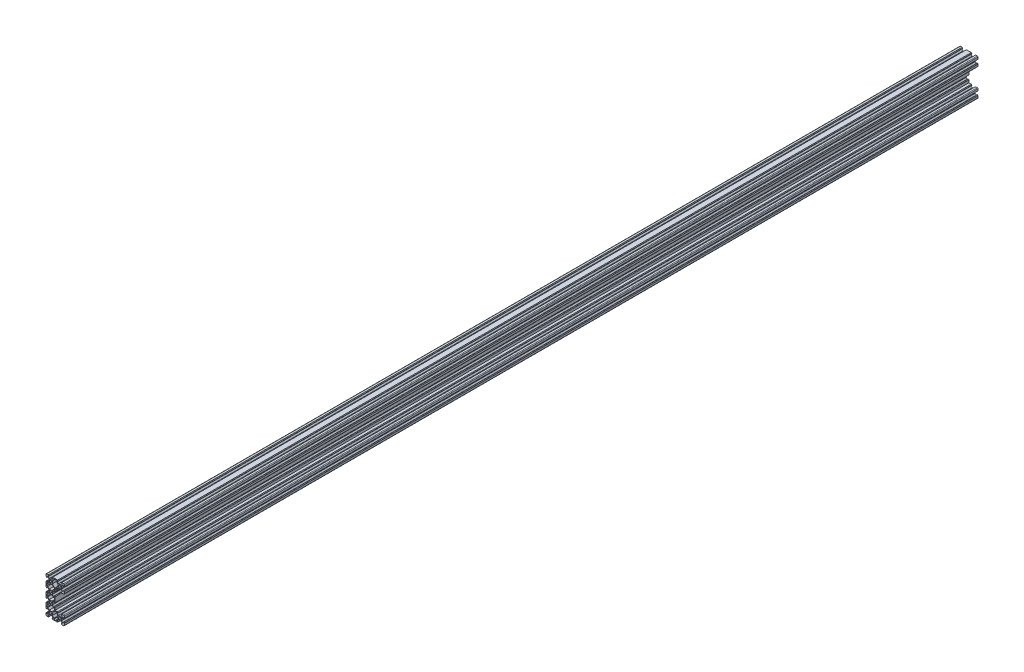
SolidWorks part; units mm, degrees
material "Aluminium"
ref_plane "Front Plane" through (0, 0, 0) normal (0, 0, 1) x (1, 0, 0)
ref_plane "Top Plane" through (0, 0, 0) normal (0, 1, 0) x (1, 0, 0)
ref_plane "Right Plane" through (0, 0, 0) normal (1, 0, 0) x (0, 0, -1)
sketch "Sketch1" plane through (0, 0, 0) normal (0, 0, 1) x (1, 0, 0)
  line L0 (-20, -38.5) -> (-20, 38.5)
  line L1 (-18.5, 40) -> (18.5, 40)
  line L2 (20, 38.5) -> (20, 21.5)
  line L3 (18.5, 20) -> (0, 20)
  line L4 (0, 20) -> (0, -20)
  line L5 (0, 0) -> (-20, 0) construction
  line L6 (18.5, -20) -> (0, -20)
  line L7 (20, -38.5) -> (20, -21.5)
  line L8 (-18.5, -40) -> (18.5, -40)
  line L9 (20, 30) -> (10, 30) construction
  line L10 (-10, 0) -> (-10, 10) construction
  arc A0 (-18.5, -40) -> (-20, -38.5) centre (-18.5, -38.5) cw
  arc A1 (20, -38.5) -> (18.5, -40) centre (18.5, -38.5) cw
  arc A2 (18.5, -20) -> (20, -21.5) centre (18.5, -21.5) cw
  arc A3 (20, 21.5) -> (18.5, 20) centre (18.5, 21.5) cw
  arc A4 (18.5, 40) -> (20, 38.5) centre (18.5, 38.5) cw
  arc A5 (-20, 38.5) -> (-18.5, 40) centre (-18.5, 38.5) cw
  circle A6 centre (10, 30) radius 2.3
  circle A7 centre (-10, 30) radius 2.3
  circle A8 centre (-10, 10) radius 2.3
  circle A9 centre (-10, -10) radius 2.3
  circle A10 centre (10, -30) radius 2.3
  circle A11 centre (-10, -30) radius 2.3
  point P13 (-20, -40)
  point P16 (20, -40)
  point P19 (20, -20)
  point P22 (20, 20)
  point P25 (20, 40)
  point P28 (-20, 40)
  line B0 (-10, 30) -> (-10, 40) construction
  line B1 (-10, 33.69) -> (-10.21, 33.9)
  line B2 (-10.21, 33.9) -> (-12.8393, 33.9)
  line B3 (-12.8393, 33.9) -> (-15.5, 36.5607)
  line B4 (-15.5, 36.5607) -> (-15.5, 38.2)
  line B5 (-15.5, 38.2) -> (-13.395, 38.2)
  line B6 (-13.395, 38.2) -> (-13.395, 38.815)
  line B7 (-13.395, 38.815) -> (-14.58, 40)
  line B8 (-14.58, 40) -> (-5.42, 40)
  line B9 (-10, 30) -> (-15.9132, 35.9132) construction
  line B10 (-6.605, 38.815) -> (-5.42, 40)
  line B11 (-6.605, 38.2) -> (-6.605, 38.815)
  line B12 (-4.5, 38.2) -> (-6.605, 38.2)
  line B13 (-4.5, 36.5607) -> (-4.5, 38.2)
  line B14 (-7.1607, 33.9) -> (-4.5, 36.5607)
  line B15 (-9.79, 33.9) -> (-7.1607, 33.9)
  line B16 (-10, 33.69) -> (-9.79, 33.9)
  line B17 (10, 30) -> (10, 40) construction
  line B18 (10, 33.69) -> (9.79, 33.9)
  line B19 (9.79, 33.9) -> (7.1607, 33.9)
  line B20 (7.1607, 33.9) -> (4.5, 36.5607)
  line B21 (4.5, 36.5607) -> (4.5, 38.2)
  line B22 (4.5, 38.2) -> (6.605, 38.2)
  line B23 (6.605, 38.2) -> (6.605, 38.815)
  line B24 (6.605, 38.815) -> (5.42, 40)
  line B25 (5.42, 40) -> (14.58, 40)
  line B26 (10, 30) -> (4.0868, 35.9132) construction
  line B27 (13.395, 38.815) -> (14.58, 40)
  line B28 (13.395, 38.2) -> (13.395, 38.815)
  line B29 (15.5, 38.2) -> (13.395, 38.2)
  line B30 (15.5, 36.5607) -> (15.5, 38.2)
  line B31 (12.8393, 33.9) -> (15.5, 36.5607)
  line B32 (10.21, 33.9) -> (12.8393, 33.9)
  line B33 (10, 33.69) -> (10.21, 33.9)
  line B34 (10, -30) -> (10, -20) construction
  line B35 (10, -26.31) -> (9.79, -26.1)
  line B36 (9.79, -26.1) -> (7.1607, -26.1)
  line B37 (7.1607, -26.1) -> (4.5, -23.4393)
  line B38 (4.5, -23.4393) -> (4.5, -21.8)
  line B39 (4.5, -21.8) -> (6.605, -21.8)
  line B40 (6.605, -21.8) -> (6.605, -21.185)
  line B41 (6.605, -21.185) -> (5.42, -20)
  line B42 (5.42, -20) -> (14.58, -20)
  line B43 (10, -30) -> (4.0868, -24.0868) construction
  line B44 (13.395, -21.185) -> (14.58, -20)
  line B45 (13.395, -21.8) -> (13.395, -21.185)
  line B46 (15.5, -21.8) -> (13.395, -21.8)
  line B47 (15.5, -23.4393) -> (15.5, -21.8)
  line B48 (12.8393, -26.1) -> (15.5, -23.4393)
  line B49 (10.21, -26.1) -> (12.8393, -26.1)
  line B50 (10, -26.31) -> (10.21, -26.1)
  line B51 (-10, 30) -> (-20, 30) construction
  line B52 (-13.69, 30) -> (-13.9, 29.79)
  line B53 (-13.9, 29.79) -> (-13.9, 27.1607)
  line B54 (-13.9, 27.1607) -> (-16.5607, 24.5)
  line B55 (-16.5607, 24.5) -> (-18.2, 24.5)
  line B56 (-18.2, 24.5) -> (-18.2, 26.605)
  line B57 (-18.2, 26.605) -> (-18.815, 26.605)
  line B58 (-18.815, 26.605) -> (-20, 25.42)
  line B59 (-20, 25.42) -> (-20, 34.58)
  line B60 (-10, 30) -> (-15.9132, 24.0868) construction
  line B61 (-18.815, 33.395) -> (-20, 34.58)
  line B62 (-18.2, 33.395) -> (-18.815, 33.395)
  line B63 (-18.2, 35.5) -> (-18.2, 33.395)
  line B64 (-16.5607, 35.5) -> (-18.2, 35.5)
  line B65 (-13.9, 32.8393) -> (-16.5607, 35.5)
  line B66 (-13.9, 30.21) -> (-13.9, 32.8393)
  line B67 (-13.69, 30) -> (-13.9, 30.21)
  line B68 (-10, 10) -> (-20, 10) construction
  line B69 (-13.69, 10) -> (-13.9, 9.79)
  line B70 (-13.9, 9.79) -> (-13.9, 7.1607)
  line B71 (-13.9, 7.1607) -> (-16.5607, 4.5)
  line B72 (-16.5607, 4.5) -> (-18.2, 4.5)
  line B73 (-18.2, 4.5) -> (-18.2, 6.605)
  line B74 (-18.2, 6.605) -> (-18.815, 6.605)
  line B75 (-18.815, 6.605) -> (-20, 5.42)
  line B76 (-20, 5.42) -> (-20, 14.58)
  line B77 (-10, 10) -> (-15.9132, 4.0868) construction
  line B78 (-18.815, 13.395) -> (-20, 14.58)
  line B79 (-18.2, 13.395) -> (-18.815, 13.395)
  line B80 (-18.2, 15.5) -> (-18.2, 13.395)
  line B81 (-16.5607, 15.5) -> (-18.2, 15.5)
  line B82 (-13.9, 12.8393) -> (-16.5607, 15.5)
  line B83 (-13.9, 10.21) -> (-13.9, 12.8393)
  line B84 (-13.69, 10) -> (-13.9, 10.21)
  line B85 (-10, -10) -> (-20, -10) construction
  line B86 (-13.69, -10) -> (-13.9, -10.21)
  line B87 (-13.9, -10.21) -> (-13.9, -12.8393)
  line B88 (-13.9, -12.8393) -> (-16.5607, -15.5)
  line B89 (-16.5607, -15.5) -> (-18.2, -15.5)
  line B90 (-18.2, -15.5) -> (-18.2, -13.395)
  line B91 (-18.2, -13.395) -> (-18.815, -13.395)
  line B92 (-18.815, -13.395) -> (-20, -14.58)
  line B93 (-20, -14.58) -> (-20, -5.42)
  line B94 (-10, -10) -> (-15.9132, -15.9132) construction
  line B95 (-18.815, -6.605) -> (-20, -5.42)
  line B96 (-18.2, -6.605) -> (-18.815, -6.605)
  line B97 (-18.2, -4.5) -> (-18.2, -6.605)
  line B98 (-16.5607, -4.5) -> (-18.2, -4.5)
  line B99 (-13.9, -7.1607) -> (-16.5607, -4.5)
  line B100 (-13.9, -9.79) -> (-13.9, -7.1607)
  line B101 (-13.69, -10) -> (-13.9, -9.79)
  line B102 (-10, -30) -> (-20, -30) construction
  line B103 (-13.69, -30) -> (-13.9, -30.21)
  line B104 (-13.9, -30.21) -> (-13.9, -32.8393)
  line B105 (-13.9, -32.8393) -> (-16.5607, -35.5)
  line B106 (-16.5607, -35.5) -> (-18.2, -35.5)
  line B107 (-18.2, -35.5) -> (-18.2, -33.395)
  line B108 (-18.2, -33.395) -> (-18.815, -33.395)
  line B109 (-18.815, -33.395) -> (-20, -34.58)
  line B110 (-20, -34.58) -> (-20, -25.42)
  line B111 (-10, -30) -> (-15.9132, -35.9132) construction
  line B112 (-18.815, -26.605) -> (-20, -25.42)
  line B113 (-18.2, -26.605) -> (-18.815, -26.605)
  line B114 (-18.2, -24.5) -> (-18.2, -26.605)
  line B115 (-16.5607, -24.5) -> (-18.2, -24.5)
  line B116 (-13.9, -27.1607) -> (-16.5607, -24.5)
  line B117 (-13.9, -29.79) -> (-13.9, -27.1607)
  line B118 (-13.69, -30) -> (-13.9, -29.79)
  line B119 (-10, -30) -> (-10, -40) construction
  line B120 (-10, -33.69) -> (-9.79, -33.9)
  line B121 (-9.79, -33.9) -> (-7.1607, -33.9)
  line B122 (-7.1607, -33.9) -> (-4.5, -36.5607)
  line B123 (-4.5, -36.5607) -> (-4.5, -38.2)
  line B124 (-4.5, -38.2) -> (-6.605, -38.2)
  line B125 (-6.605, -38.2) -> (-6.605, -38.815)
  line B126 (-6.605, -38.815) -> (-5.42, -40)
  line B127 (-5.42, -40) -> (-14.58, -40)
  line B128 (-10, -30) -> (-4.0868, -35.9132) construction
  line B129 (-13.395, -38.815) -> (-14.58, -40)
  line B130 (-13.395, -38.2) -> (-13.395, -38.815)
  line B131 (-15.5, -38.2) -> (-13.395, -38.2)
  line B132 (-15.5, -36.5607) -> (-15.5, -38.2)
  line B133 (-12.8393, -33.9) -> (-15.5, -36.5607)
  line B134 (-10.21, -33.9) -> (-12.8393, -33.9)
  line B135 (-10, -33.69) -> (-10.21, -33.9)
  line B136 (10, -30) -> (10, -40) construction
  line B137 (10, -33.69) -> (10.21, -33.9)
  line B138 (10.21, -33.9) -> (12.8393, -33.9)
  line B139 (12.8393, -33.9) -> (15.5, -36.5607)
  line B140 (15.5, -36.5607) -> (15.5, -38.2)
  line B141 (15.5, -38.2) -> (13.395, -38.2)
  line B142 (13.395, -38.2) -> (13.395, -38.815)
  line B143 (13.395, -38.815) -> (14.58, -40)
  line B144 (14.58, -40) -> (5.42, -40)
  line B145 (10, -30) -> (15.9132, -35.9132) construction
  line B146 (6.605, -38.815) -> (5.42, -40)
  line B147 (6.605, -38.2) -> (6.605, -38.815)
  line B148 (4.5, -38.2) -> (6.605, -38.2)
  line B149 (4.5, -36.5607) -> (4.5, -38.2)
  line B150 (7.1607, -33.9) -> (4.5, -36.5607)
  line B151 (9.79, -33.9) -> (7.1607, -33.9)
  line B152 (10, -33.69) -> (9.79, -33.9)
  line B153 (10, 30) -> (10, 20) construction
  line B154 (10, 26.31) -> (10.21, 26.1)
  line B155 (10.21, 26.1) -> (12.8393, 26.1)
  line B156 (12.8393, 26.1) -> (15.5, 23.4393)
  line B157 (15.5, 23.4393) -> (15.5, 21.8)
  line B158 (15.5, 21.8) -> (13.395, 21.8)
  line B159 (13.395, 21.8) -> (13.395, 21.185)
  line B160 (13.395, 21.185) -> (14.58, 20)
  line B161 (14.58, 20) -> (5.42, 20)
  line B162 (10, 30) -> (15.9132, 24.0868) construction
  line B163 (6.605, 21.185) -> (5.42, 20)
  line B164 (6.605, 21.8) -> (6.605, 21.185)
  line B165 (4.5, 21.8) -> (6.605, 21.8)
  line B166 (4.5, 23.4393) -> (4.5, 21.8)
  line B167 (7.1607, 26.1) -> (4.5, 23.4393)
  line B168 (9.79, 26.1) -> (7.1607, 26.1)
  line B169 (10, 26.31) -> (9.79, 26.1)
  line B170 (-10, 10) -> (0, 10) construction
  line B171 (-6.31, 10) -> (-6.1, 10.21)
  line B172 (-6.1, 10.21) -> (-6.1, 12.8393)
  line B173 (-6.1, 12.8393) -> (-3.4393, 15.5)
  line B174 (-3.4393, 15.5) -> (-1.8, 15.5)
  line B175 (-1.8, 15.5) -> (-1.8, 13.395)
  line B176 (-1.8, 13.395) -> (-1.185, 13.395)
  line B177 (-1.185, 13.395) -> (0, 14.58)
  line B178 (0, 14.58) -> (0, 5.42)
  line B179 (-10, 10) -> (-4.0868, 15.9132) construction
  line B180 (-1.185, 6.605) -> (0, 5.42)
  line B181 (-1.8, 6.605) -> (-1.185, 6.605)
  line B182 (-1.8, 4.5) -> (-1.8, 6.605)
  line B183 (-3.4393, 4.5) -> (-1.8, 4.5)
  line B184 (-6.1, 7.1607) -> (-3.4393, 4.5)
  line B185 (-6.1, 9.79) -> (-6.1, 7.1607)
  line B186 (-6.31, 10) -> (-6.1, 9.79)
  line B187 (-10, -10) -> (0, -10) construction
  line B188 (-6.31, -10) -> (-6.1, -9.79)
  line B189 (-6.1, -9.79) -> (-6.1, -7.1607)
  line B190 (-6.1, -7.1607) -> (-3.4393, -4.5)
  line B191 (-3.4393, -4.5) -> (-1.8, -4.5)
  line B192 (-1.8, -4.5) -> (-1.8, -6.605)
  line B193 (-1.8, -6.605) -> (-1.185, -6.605)
  line B194 (-1.185, -6.605) -> (0, -5.42)
  line B195 (0, -5.42) -> (0, -14.58)
  line B196 (-10, -10) -> (-4.0868, -4.0868) construction
  line B197 (-1.185, -13.395) -> (0, -14.58)
  line B198 (-1.8, -13.395) -> (-1.185, -13.395)
  line B199 (-1.8, -15.5) -> (-1.8, -13.395)
  line B200 (-3.4393, -15.5) -> (-1.8, -15.5)
  line B201 (-6.1, -12.8393) -> (-3.4393, -15.5)
  line B202 (-6.1, -10.21) -> (-6.1, -12.8393)
  line B203 (-6.31, -10) -> (-6.1, -10.21)
  line B204 (10, -30) -> (20, -30) construction
  line B205 (13.69, -30) -> (13.9, -29.79)
  line B206 (13.9, -29.79) -> (13.9, -27.1607)
  line B207 (13.9, -27.1607) -> (16.5607, -24.5)
  line B208 (16.5607, -24.5) -> (18.2, -24.5)
  line B209 (18.2, -24.5) -> (18.2, -26.605)
  line B210 (18.2, -26.605) -> (18.815, -26.605)
  line B211 (18.815, -26.605) -> (20, -25.42)
  line B212 (20, -25.42) -> (20, -34.58)
  line B213 (10, -30) -> (15.9132, -24.0868) construction
  line B214 (18.815, -33.395) -> (20, -34.58)
  line B215 (18.2, -33.395) -> (18.815, -33.395)
  line B216 (18.2, -35.5) -> (18.2, -33.395)
  line B217 (16.5607, -35.5) -> (18.2, -35.5)
  line B218 (13.9, -32.8393) -> (16.5607, -35.5)
  line B219 (13.9, -30.21) -> (13.9, -32.8393)
  line B220 (13.69, -30) -> (13.9, -30.21)
  line B221 (10, 30) -> (20, 30) construction
  line B222 (13.69, 30) -> (13.9, 30.21)
  line B223 (13.9, 30.21) -> (13.9, 32.8393)
  line B224 (13.9, 32.8393) -> (16.5607, 35.5)
  line B225 (16.5607, 35.5) -> (18.2, 35.5)
  line B226 (18.2, 35.5) -> (18.2, 33.395)
  line B227 (18.2, 33.395) -> (18.815, 33.395)
  line B228 (18.815, 33.395) -> (20, 34.58)
  line B229 (20, 34.58) -> (20, 25.42)
  line B230 (10, 30) -> (15.9132, 35.9132) construction
  line B231 (18.815, 26.605) -> (20, 25.42)
  line B232 (18.2, 26.605) -> (18.815, 26.605)
  line B233 (18.2, 24.5) -> (18.2, 26.605)
  line B234 (16.5607, 24.5) -> (18.2, 24.5)
  line B235 (13.9, 27.1607) -> (16.5607, 24.5)
  line B236 (13.9, 29.79) -> (13.9, 27.1607)
  line B237 (13.69, 30) -> (13.9, 29.79)
  line B238 (-18.2, -2.7) -> (-18.2, 2.7)
  line B239 (-18.2, 2.7) -> (-16.2393, 2.7)
  line B240 (-16.2393, 2.7) -> (-12.8393, 6.1)
  line B241 (-12.8393, 6.1) -> (-7.1607, 6.1)
  line B242 (-10, 6.1) -> (-10, 0) construction
  line B243 (-10, 0) -> (-18.2, 0) construction
  line B244 (-3.7607, 2.7) -> (-7.1607, 6.1)
  line B245 (-1.8, 2.7) -> (-3.7607, 2.7)
  line B246 (-1.8, -2.7) -> (-1.8, 2.7)
  line B247 (-1.8, -2.7) -> (-3.7607, -2.7)
  line B248 (-3.7607, -2.7) -> (-7.1607, -6.1)
  line B249 (-12.8393, -6.1) -> (-7.1607, -6.1)
  line B250 (-16.2393, -2.7) -> (-12.8393, -6.1)
  line B251 (-18.2, -2.7) -> (-16.2393, -2.7)
  line B252 (-10, 6.1) -> (-10, 10) construction
  line B253 (-10, 10) -> (-15.0927, 4.9073) construction
  line B254 (-18.2, 17.3) -> (-18.2, 22.7)
  line B255 (-18.2, 22.7) -> (-16.2393, 22.7)
  line B256 (-16.2393, 22.7) -> (-12.8393, 26.1)
  line B257 (-12.8393, 26.1) -> (-7.1607, 26.1)
  line B258 (-10, 26.1) -> (-10, 20) construction
  line B259 (-10, 20) -> (-18.2, 20) construction
  line B260 (-1.8, 17.3) -> (-3.7607, 17.3)
  line B261 (-3.7607, 17.3) -> (-7.1607, 13.9)
  line B262 (-12.8393, 13.9) -> (-7.1607, 13.9)
  line B263 (-16.2393, 17.3) -> (-12.8393, 13.9)
  line B264 (-18.2, 17.3) -> (-16.2393, 17.3)
  line B265 (-10, 26.1) -> (-10, 30) construction
  line B266 (-10, 30) -> (-15.0927, 24.9073) construction
  line B267 (-7.1607, 26.1) -> (-1.8, 20.7393)
  line B268 (-1.8, 17.3) -> (-1.8, 20.7393)
  line B269 (2.7, -38.2) -> (-2.7, -38.2)
  line B270 (-2.7, -38.2) -> (-2.7, -36.2393)
  line B271 (-2.7, -36.2393) -> (-6.1, -32.8393)
  line B272 (-6.1, -32.8393) -> (-6.1, -27.1607)
  line B273 (-6.1, -30) -> (0, -30) construction
  line B274 (0, -30) -> (0, -38.2) construction
  line B275 (2.7, -21.8) -> (2.7, -23.7607)
  line B276 (2.7, -23.7607) -> (6.1, -27.1607)
  line B277 (6.1, -32.8393) -> (6.1, -27.1607)
  line B278 (2.7, -36.2393) -> (6.1, -32.8393)
  line B279 (2.7, -38.2) -> (2.7, -36.2393)
  line B280 (-6.1, -30) -> (-10, -30) construction
  line B281 (-10, -30) -> (-4.9073, -35.0927) construction
  line B282 (-6.1, -27.1607) -> (-0.7393, -21.8)
  line B283 (2.7, -21.8) -> (-0.7393, -21.8)
  line B284 (-18.2, -22.7) -> (-18.2, -17.3)
  line B285 (-18.2, -17.3) -> (-16.2393, -17.3)
  line B286 (-16.2393, -17.3) -> (-12.8393, -13.9)
  line B287 (-12.8393, -13.9) -> (-7.1607, -13.9)
  line B288 (-10, -13.9) -> (-10, -20) construction
  line B289 (-10, -20) -> (-18.2, -20) construction
  line B290 (-12.8393, -26.1) -> (-7.1607, -26.1)
  line B291 (-16.2393, -22.7) -> (-12.8393, -26.1)
  line B292 (-18.2, -22.7) -> (-16.2393, -22.7)
  line B293 (-10, -13.9) -> (-10, -10) construction
  line B294 (-10, -10) -> (-15.0927, -15.0927) construction
  line B295 (-3.7607, -17.3) -> (-7.1607, -13.9)
  line B296 (-1.8, -17.3) -> (-3.7607, -17.3)
  line B297 (-1.8, -17.3) -> (-1.8, -20.7393)
  line B298 (-1.8, -20.7393) -> (-7.1607, -26.1)
  line B299 (-2.7, 38.2) -> (2.7, 38.2)
  line B300 (2.7, 38.2) -> (2.7, 36.2393)
  line B301 (2.7, 36.2393) -> (6.1, 32.8393)
  line B302 (6.1, 32.8393) -> (6.1, 27.1607)
  line B303 (6.1, 30) -> (0, 30) construction
  line B304 (0, 30) -> (0, 38.2) construction
  line B305 (-6.1, 32.8393) -> (-6.1, 27.1607)
  line B306 (-2.7, 36.2393) -> (-6.1, 32.8393)
  line B307 (-2.7, 38.2) -> (-2.7, 36.2393)
  line B308 (6.1, 30) -> (10, 30) construction
  line B309 (10, 30) -> (4.9073, 35.0927) construction
  line B310 (2.7, 23.7607) -> (6.1, 27.1607)
  line B311 (2.7, 21.8) -> (2.7, 23.7607)
  line B312 (2.7, 21.8) -> (-0.7393, 21.8)
  line B313 (-0.7393, 21.8) -> (-6.1, 27.1607)
  dimension "D3" = 1.5
  dimension "D6" = 4.6
  dimension "D7" = 20
  dimension "D8" = 20
  dimension "D1" = 40
  dimension "D2" = 80
  dimension "D4" = 20
  dimension "D5" = 20
sketch_block_instance "V Slot 2-1"
sketch_block "V Slot 2" parameters "D1"=10, "D2"=11, "D3"=4.3, "D4"=1.8, "D5"=0.21, "D6"=45, "D7"=9.16, "D8"=1.5, "D9"=6.79
sketch_block_instance "V Slot 2-2"
sketch_block_instance "V Slot 2-3"
sketch_block_instance "V Slot 2-4"
sketch_block_instance "V Slot 2-5"
sketch_block_instance "V Slot 2-6"
sketch_block_instance "V Slot 2-7"
sketch_block_instance "V Slot 2-8"
sketch_block_instance "V Slot 2-9"
sketch_block_instance "V Slot 2-10"
sketch_block_instance "V Slot 2-11"
sketch_block_instance "V Slot 2-12"
sketch_block_instance "V Slot 2-13"
sketch_block_instance "V Slot 2-14"
sketch_block_instance "Center Cutout 1-1"
sketch_block "Center Cutout 1" parameters "D1"=5.4, "D2"=12.2, "D3"=8.2, "D4"=45, "D5"=10, "D6"=1.5
sketch_block_instance "Corner Cutout 1-1"
sketch_block "Corner Cutout 1" parameters "D1"=5.4, "D2"=12.2, "D3"=8.2, "D4"=45, "D5"=10, "D6"=1.5
sketch_block_instance "Corner Cutout 1-2"
sketch_block_instance "Corner Cutout 2-1"
sketch_block "Corner Cutout 2" parameters "D1"=5.4, "D2"=12.2, "D3"=8.2, "D4"=45, "D5"=10, "D6"=1.5
sketch_block_instance "Corner Cutout 2-2"
extrude "Boss-Extrude1" add sketch "Sketch1" along normal mid plane 2000 contours B237 B222 B223 B224 B225 B226 B227 B228 L2 A4 L1 B27 B28 B29 B30 B31 B32 B33 B18 B19 B20 B21 B22 B23 B24 B10 B11 B12 B13 B14 B15 B16 B1 B2 B3 B4 B5 B6 B7 A5 L0 B61 B62 B63 B64 B65 B66 B67 B52
